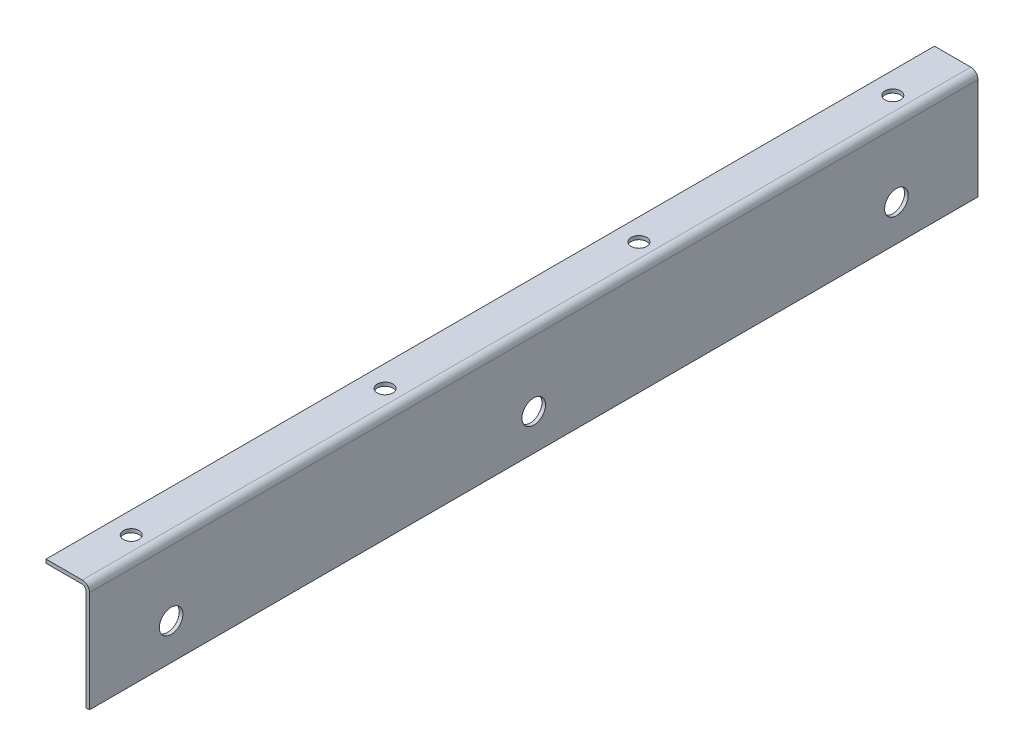
SolidWorks part; units mm, degrees
ref_plane "Спереди" through (0, 0, 0) normal (0, 0, 1) x (1, 0, 0)
ref_plane "Сверху" through (0, 0, 0) normal (0, 1, 0) x (1, 0, 0)
ref_plane "Справа" through (0, 0, 0) normal (1, 0, 0) x (0, 0, -1)
sketch "Эскиз1" plane through (0, 0, 0) normal (0, 0, 1) x (1, 0, 0)
  line L0 (0, 0) -> (0, 35.984) construction
  line L1 (0, 0) -> (37.3399, 0) construction
  line L2 (-1, -2) -> (-1, -30)
  line L3 (-2, 0) -> (-12, 0)
  line L4 (0, -2) -> (0, -30)
  line L5 (-2, -1) -> (-12, -1)
  line L6 (-1, -30) -> (0, -30)
  line L7 (-12, 0) -> (-12, -1)
  arc A0 (-2, 0) -> (0, -2) centre (-2, -2) cw
  arc A1 (-2, -1) -> (-1, -2) centre (-2, -2) cw
  dimension "D3" = 2
  dimension "D1" = 12
  dimension "D2" = 30
  dimension "D4" = 1
extrude "Вытянуть1" add sketch "Эскиз1" along normal blind 245
sketch "Эскиз2" plane through (0, 0, 0) normal (0, 1, 0) x (1, 0, 0)
  line L0 (-6, 13.6956) -> (-6, -249.0337) construction
  line L1 (-12, -245) -> (-12, 0) construction
  line L2 (-2, -245) -> (-12, -245) construction
  circle A0 centre (-6, -17.5) radius 2.15
  circle A1 centre (-6, -87.5) radius 2.15
  circle A2 centre (-6, -157.5) radius 2.15
  circle A3 centre (-6, -227.5) radius 2.15
  dimension "D2" = 4.3
  dimension "D3" = 17.5
  dimension "D4" = 70
  dimension "D5" = 70
  dimension "D6" = 70
  dimension "D1" = 6
extrude "Вырез-Вытянуть1" cut sketch "Эскиз2" against normal blind 245
sketch "Эскиз3" plane through (0, 0, 0) normal (1, 0, 0) x (0, 0, -1)
  line L0 (-250.8579, -20) -> (4.4222, -20) construction
  line L1 (-245, 0) -> (0, 0) construction
  line L2 (-122.5, 29.3653) -> (-122.5, -65.1363) construction
  line L3 (-245, -30) -> (-245, -2) construction
  line L4 (0, -30) -> (0, -2) construction
  circle A0 centre (-122.5, -20) radius 3.25
  circle A1 centre (-22.5, -20) radius 3.25
  circle A2 centre (-222.5, -20) radius 3.25
  dimension "D2" = 6.5
  dimension "D3" = 100
  dimension "D1" = 20
extrude "Вырез-Вытянуть2" cut sketch "Эскиз3" against normal blind 245
